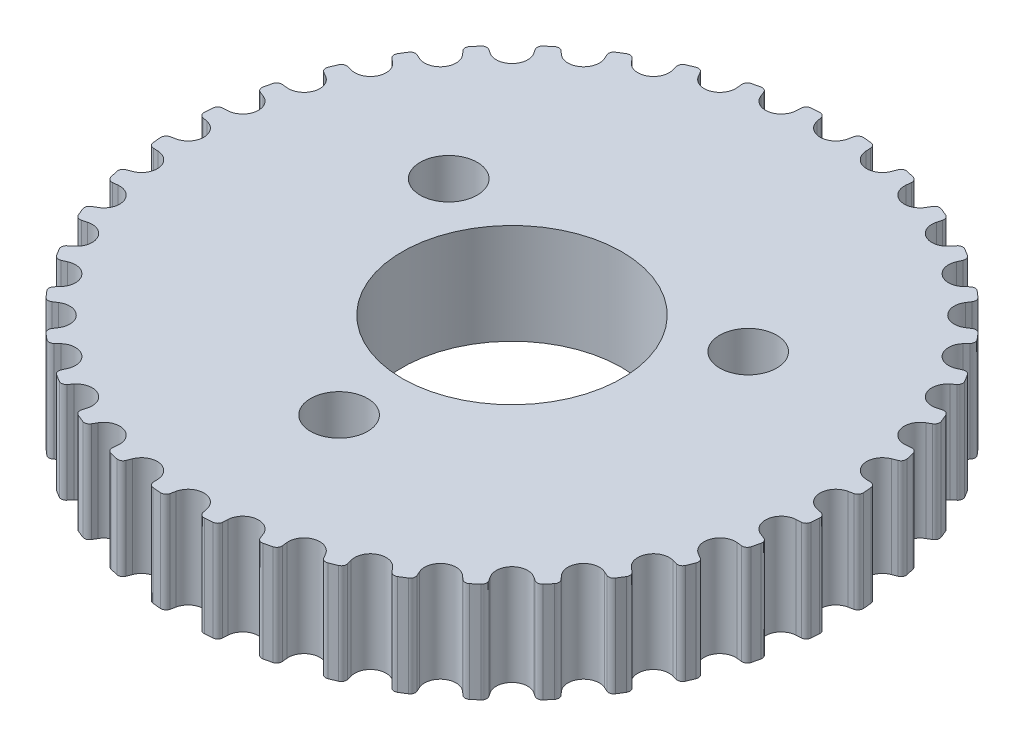
SolidWorks part; units mm, degrees
ref_plane "Front Plane" through (0, 0, 0) normal (0, 0, 1) x (1, 0, 0)
ref_plane "Top Plane" through (0, 0, 0) normal (0, 1, 0) x (1, 0, 0)
ref_plane "Right Plane" through (0, 0, 0) normal (1, 0, 0) x (0, 0, -1)
sketch "Sketch1" plane through (0, 0, 0) normal (0, 1, 0) x (1, 0, 0)
  circle A0 centre (0, 0) radius 19.0986
  dimension "D1" = 38.1972
extrude "Boss-Extrude1" add sketch "Sketch1" along normal blind 5.8
sketch "Sketch2" plane through (0, 5.8, 0) normal (0, 1, 0) x (1, 0, 0)
  line L0 (0, 0) -> (0, 19.0986) construction
  line L1 (-0.89, 18.5387) -> (-0.95, 18.82)
  line L2 (-2.9877, 18.8635) -> (-2.9877, 19.0986)
  line L3 (-2.9877, 19.0986) -> (2.9877, 19.0986)
  line L4 (0.89, 18.5387) -> (0.95, 18.82)
  line L5 (2.9877, 18.8635) -> (2.9877, 19.0986)
  circle A0 centre (0, 0) radius 19.0986 construction
  arc A1 (0.89, 18.5387) -> (-0.89, 18.5387) centre (0, 18.7286) cw
  arc A2 (-0.95, 18.82) -> (-1.2632, 19.0568) centre (-1.2434, 18.7574) ccw
  arc A4 (0.95, 18.82) -> (1.2632, 19.0568) centre (1.2434, 18.7574) cw
  arc A5 (-1.2632, 19.0568) -> (-2.9877, 18.8635) centre (0, 0) ccw
  arc A6 (1.2632, 19.0568) -> (2.9877, 18.8635) centre (0, 0) cw
  circle A8 centre (0, 0) radius 19.0986 construction
  point P11 (0, 19.0986)
  point P19 (0, 17.8186)
  dimension "D3" = 0.3
  dimension "D5" = 0.91
  dimension "D2" = 0.95
  dimension "D4" = 1.28
  dimension "D6" = 9
extrude "Cut-Extrude1" cut sketch "Sketch2" against normal through all
pattern_circular "CirPattern1" count 40 over 360 about axis through (0, 0, 0) along (0, 1, 0) of "Cut-Extrude1"
sketch "Sketch3" plane through (0, 0, 0) normal (0, -1, 0) x (1, 0, 0)
  circle A0 centre (0, 0) radius 6.35
  dimension "D1" = 12.7
extrude "Cut-Extrude2" cut sketch "Sketch3" against normal through all
sketch "Sketch4" plane through (0, 0, 0) normal (0, -1, 0) x (1, 0, 0)
  line L0 (0, 0) -> (0, 10) construction
  circle A0 centre (0, 10) radius 1.65
  circle A1 centre (8.6603, -5) radius 1.65
  circle A2 centre (-8.6603, -5) radius 1.65
  point P14 (0, 0)
  dimension "D1" = 3.3
  dimension "D2" = 10
  dimension "D3" = 3
extrude "Cut-Extrude3" cut sketch "Sketch4" against normal through all
sketch "Sketch5" plane through (0, 0, 0) normal (0, -1, 0) x (1, 0, 0)
  line L80 (-18.8409, 0.8522) -> (-18.5596, 0.7922)
  line L81 (-18.8409, 0.8522) -> (-18.5596, 0.7922)
  line L82 (-18.5596, -0.7922) -> (-18.8409, -0.8522)
  line L83 (-18.5596, -0.7922) -> (-18.8409, -0.8522)
  line L84 (-18.7423, -2.1057) -> (-18.455, -2.1209)
  line L85 (-18.7423, -2.1057) -> (-18.455, -2.1209)
  line L86 (-18.2071, -3.6858) -> (-18.4756, -3.7891)
  line L87 (-18.2071, -3.6858) -> (-18.4756, -3.7891)
  line L88 (-18.1821, -5.0117) -> (-17.896, -4.9818)
  line L89 (-18.1821, -5.0117) -> (-17.896, -4.9818)
  line L90 (-17.4064, -6.4886) -> (-17.6554, -6.6327)
  line L91 (-17.4064, -6.4886) -> (-17.6554, -6.6327)
  line L92 (-17.1743, -7.7943) -> (-16.8963, -7.72)
  line L93 (-17.1743, -7.7943) -> (-16.8963, -7.72)
  line L94 (-16.177, -9.1317) -> (-16.4005, -9.3129)
  line L95 (-16.177, -9.1317) -> (-16.4005, -9.3129)
  line L96 (-15.7435, -10.385) -> (-15.4806, -10.2682)
  line L97 (-15.7435, -10.385) -> (-15.4806, -10.2682)
  line L98 (-14.5494, -11.5499) -> (-14.7417, -11.7639)
  line L99 (-14.5494, -11.5499) -> (-14.7417, -11.7639)
  line L100 (-13.9251, -12.7199) -> (-13.6837, -12.5634)
  line L101 (-13.9251, -12.7199) -> (-13.6837, -12.5634)
  line L102 (-12.5634, -13.6837) -> (-12.7199, -13.9251)
  line L103 (-12.5634, -13.6837) -> (-12.7199, -13.9251)
  line L104 (-11.7639, -14.7417) -> (-11.5499, -14.5494)
  line L105 (-11.7639, -14.7417) -> (-11.5499, -14.5494)
  line L106 (-10.2682, -15.4806) -> (-10.385, -15.7435)
  line L107 (-10.2682, -15.4806) -> (-10.385, -15.7435)
  line L108 (-9.3129, -16.4005) -> (-9.1317, -16.177)
  line L109 (-9.3129, -16.4005) -> (-9.1317, -16.177)
  line L110 (-7.72, -16.8963) -> (-7.7943, -17.1743)
  line L111 (-7.72, -16.8963) -> (-7.7943, -17.1743)
  line L112 (-6.6327, -17.6554) -> (-6.4886, -17.4064)
  line L113 (-6.6327, -17.6554) -> (-6.4886, -17.4064)
  line L114 (-4.9818, -17.896) -> (-5.0117, -18.1821)
  line L115 (-4.9818, -17.896) -> (-5.0117, -18.1821)
  line L116 (-3.7891, -18.4756) -> (-3.6858, -18.2071)
  line L117 (-3.7891, -18.4756) -> (-3.6858, -18.2071)
  line L118 (-2.1209, -18.455) -> (-2.1057, -18.7423)
  line L119 (-2.1209, -18.455) -> (-2.1057, -18.7423)
  line L120 (6.4886, -17.4064) -> (6.6327, -17.6554)
  line L121 (7.7943, -17.1743) -> (7.72, -16.8963)
  line L122 (9.1317, -16.177) -> (9.3129, -16.4005)
  line L123 (10.385, -15.7435) -> (10.2682, -15.4806)
  line L124 (11.5499, -14.5494) -> (11.7639, -14.7417)
  line L125 (12.7199, -13.9251) -> (12.5634, -13.6837)
  line L126 (13.6837, -12.5634) -> (13.9251, -12.7199)
  line L127 (14.7417, -11.7639) -> (14.5494, -11.5499)
  line L128 (15.4806, -10.2682) -> (15.7435, -10.385)
  line L129 (16.4005, -9.3129) -> (16.177, -9.1317)
  line L130 (16.8963, -7.72) -> (17.1743, -7.7943)
  line L131 (17.6554, -6.6327) -> (17.4064, -6.4886)
  line L132 (17.896, -4.9818) -> (18.1821, -5.0117)
  line L133 (18.4756, -3.7891) -> (18.2071, -3.6858)
  line L134 (18.455, -2.1209) -> (18.7423, -2.1057)
  line L135 (18.8409, -0.8522) -> (18.5596, -0.7922)
  line L136 (18.5596, 0.7922) -> (18.8409, 0.8522)
  line L137 (18.7423, 2.1057) -> (18.455, 2.1209)
  line L138 (18.2071, 3.6858) -> (18.4756, 3.7891)
  line L139 (18.1821, 5.0117) -> (17.896, 4.9818)
  line L140 (17.4064, 6.4886) -> (17.6554, 6.6327)
  line L141 (17.1743, 7.7943) -> (16.8963, 7.72)
  line L142 (16.177, 9.1317) -> (16.4005, 9.3129)
  line L143 (15.7435, 10.385) -> (15.4806, 10.2682)
  line L144 (14.5494, 11.5499) -> (14.7417, 11.7639)
  line L145 (13.9251, 12.7199) -> (13.6837, 12.5634)
  line L146 (12.5634, 13.6837) -> (12.7199, 13.9251)
  line L147 (11.7639, 14.7417) -> (11.5499, 14.5494)
  line L148 (10.2682, 15.4806) -> (10.385, 15.7435)
  line L149 (9.3129, 16.4005) -> (9.1317, 16.177)
  line L150 (7.72, 16.8963) -> (7.7943, 17.1743)
  line L151 (6.6327, 17.6554) -> (6.4886, 17.4064)
  line L152 (4.9818, 17.896) -> (5.0117, 18.1821)
  line L153 (3.7891, 18.4756) -> (3.6858, 18.2071)
  line L154 (2.1209, 18.455) -> (2.1057, 18.7423)
  line L155 (0.8522, 18.8409) -> (0.7922, 18.5596)
  line L156 (-0.7922, 18.5596) -> (-0.8522, 18.8409)
  line L157 (-2.1057, 18.7423) -> (-2.1209, 18.455)
  line L158 (-3.6858, 18.2071) -> (-3.7891, 18.4756)
  line L159 (-5.0117, 18.1821) -> (-4.9818, 17.896)
  line L160 (-6.4886, 17.4064) -> (-6.6327, 17.6554)
  line L161 (-7.7943, 17.1743) -> (-7.72, 16.8963)
  line L162 (-9.1317, 16.177) -> (-9.3129, 16.4005)
  line L163 (-10.385, 15.7435) -> (-10.2682, 15.4806)
  line L164 (-11.5499, 14.5494) -> (-11.7639, 14.7417)
  line L165 (-12.7199, 13.9251) -> (-12.5634, 13.6837)
  line L166 (-13.6837, 12.5634) -> (-13.9251, 12.7199)
  line L167 (-14.7417, 11.7639) -> (-14.5494, 11.5499)
  line L168 (-15.4806, 10.2682) -> (-15.7435, 10.385)
  line L169 (-16.4005, 9.3129) -> (-16.177, 9.1317)
  line L170 (-16.8963, 7.72) -> (-17.1743, 7.7943)
  line L171 (-17.6554, 6.6327) -> (-17.4064, 6.4886)
  line L172 (-17.896, 4.9818) -> (-18.1821, 5.0117)
  line L173 (-18.4756, 3.7891) -> (-18.2071, 3.6858)
  line L174 (-18.455, 2.1209) -> (-18.7423, 2.1057)
  line L175 (-0.8522, -18.8409) -> (-0.7922, -18.5596)
  line L176 (0.7922, -18.5596) -> (0.8522, -18.8409)
  line L177 (2.1057, -18.7423) -> (2.1209, -18.455)
  line L178 (3.6858, -18.2071) -> (3.7891, -18.4756)
  line L179 (5.0117, -18.1821) -> (4.9818, -17.896)
  line L180 (6.4886, -17.4064) -> (6.6327, -17.6554)
  line L181 (7.7943, -17.1743) -> (7.72, -16.8963)
  line L182 (9.1317, -16.177) -> (9.3129, -16.4005)
  line L183 (10.385, -15.7435) -> (10.2682, -15.4806)
  line L184 (11.5499, -14.5494) -> (11.7639, -14.7417)
  line L185 (12.7199, -13.9251) -> (12.5634, -13.6837)
  line L186 (13.6837, -12.5634) -> (13.9251, -12.7199)
  line L187 (14.7417, -11.7639) -> (14.5494, -11.5499)
  line L188 (15.4806, -10.2682) -> (15.7435, -10.385)
  line L189 (16.4005, -9.3129) -> (16.177, -9.1317)
  line L190 (16.8963, -7.72) -> (17.1743, -7.7943)
  line L191 (17.6554, -6.6327) -> (17.4064, -6.4886)
  line L192 (17.896, -4.9818) -> (18.1821, -5.0117)
  line L193 (18.4756, -3.7891) -> (18.2071, -3.6858)
  line L194 (18.455, -2.1209) -> (18.7423, -2.1057)
  line L195 (18.8409, -0.8522) -> (18.5596, -0.7922)
  line L196 (18.5596, 0.7922) -> (18.8409, 0.8522)
  line L197 (18.7423, 2.1057) -> (18.455, 2.1209)
  line L198 (18.2071, 3.6858) -> (18.4756, 3.7891)
  line L199 (18.1821, 5.0117) -> (17.896, 4.9818)
  line L200 (17.4064, 6.4886) -> (17.6554, 6.6327)
  line L201 (17.1743, 7.7943) -> (16.8963, 7.72)
  line L202 (16.177, 9.1317) -> (16.4005, 9.3129)
  line L203 (15.7435, 10.385) -> (15.4806, 10.2682)
  line L204 (14.5494, 11.5499) -> (14.7417, 11.7639)
  line L205 (13.9251, 12.7199) -> (13.6837, 12.5634)
  line L206 (12.5634, 13.6837) -> (12.7199, 13.9251)
  line L207 (11.7639, 14.7417) -> (11.5499, 14.5494)
  line L208 (10.2682, 15.4806) -> (10.385, 15.7435)
  line L209 (9.3129, 16.4005) -> (9.1317, 16.177)
  line L210 (7.72, 16.8963) -> (7.7943, 17.1743)
  line L211 (6.6327, 17.6554) -> (6.4886, 17.4064)
  line L212 (4.9818, 17.896) -> (5.0117, 18.1821)
  line L213 (3.7891, 18.4756) -> (3.6858, 18.2071)
  line L214 (2.1209, 18.455) -> (2.1057, 18.7423)
  line L215 (0.8522, 18.8409) -> (0.7922, 18.5596)
  line L216 (-0.7922, 18.5596) -> (-0.8522, 18.8409)
  line L217 (-2.1057, 18.7423) -> (-2.1209, 18.455)
  line L218 (-3.6858, 18.2071) -> (-3.7891, 18.4756)
  line L219 (-5.0117, 18.1821) -> (-4.9818, 17.896)
  line L220 (-6.4886, 17.4064) -> (-6.6327, 17.6554)
  line L221 (-7.7943, 17.1743) -> (-7.72, 16.8963)
  line L222 (-9.1317, 16.177) -> (-9.3129, 16.4005)
  line L223 (-10.385, 15.7435) -> (-10.2682, 15.4806)
  line L224 (-11.5499, 14.5494) -> (-11.7639, 14.7417)
  line L225 (-12.7199, 13.9251) -> (-12.5634, 13.6837)
  line L226 (-13.6837, 12.5634) -> (-13.9251, 12.7199)
  line L227 (-14.7417, 11.7639) -> (-14.5494, 11.5499)
  line L228 (-15.4806, 10.2682) -> (-15.7435, 10.385)
  line L229 (-16.4005, 9.3129) -> (-16.177, 9.1317)
  line L230 (-16.8963, 7.72) -> (-17.1743, 7.7943)
  line L231 (-17.6554, 6.6327) -> (-17.4064, 6.4886)
  line L232 (-17.896, 4.9818) -> (-18.1821, 5.0117)
  line L233 (-18.4756, 3.7891) -> (-18.2071, 3.6858)
  line L234 (-18.455, 2.1209) -> (-18.7423, 2.1057)
  line L235 (-0.8522, -18.8409) -> (-0.7922, -18.5596)
  line L236 (0.7922, -18.5596) -> (0.8522, -18.8409)
  line L237 (2.1057, -18.7423) -> (2.1209, -18.455)
  line L238 (3.6858, -18.2071) -> (3.7891, -18.4756)
  line L239 (5.0117, -18.1821) -> (4.9818, -17.896)
  circle A120 centre (0, 0) radius 17.8186
  arc A121 (12.4795, 13.7381) -> (13.7381, 12.4795) centre (13.2431, 13.2431) ccw construction
  arc A162 (-19.1566, 1.2699) -> (-18.8409, 0.8522) centre (-18.7574, 1.2434) ccw
  arc A163 (-19.1566, 1.2699) -> (-18.8409, 0.8522) centre (-18.7574, 1.2434) ccw
  arc A164 (-18.5596, -0.7922) -> (-18.5596, 0.7922) centre (-18.7286, 0) ccw
  arc A165 (-18.5596, -0.7922) -> (-18.5596, 0.7922) centre (-18.7286, 0) ccw
  arc A166 (-18.8409, -0.8522) -> (-19.1566, -1.2699) centre (-18.7574, -1.2434) ccw
  arc A167 (-18.8409, -0.8522) -> (-19.1566, -1.2699) centre (-18.7574, -1.2434) ccw
  arc A168 (-19.1566, -1.2699) -> (-19.1194, -1.7425) centre (0, 0) ccw
  arc A169 (-19.1566, -1.2699) -> (-19.1194, -1.7425) centre (0, 0) ccw
  arc A170 (-19.1194, -1.7425) -> (-18.7423, -2.1057) centre (-18.721, -1.7062) ccw
  arc A171 (-19.1194, -1.7425) -> (-18.7423, -2.1057) centre (-18.721, -1.7062) ccw
  arc A172 (-18.2071, -3.6858) -> (-18.455, -2.1209) centre (-18.498, -2.9298) ccw
  arc A173 (-18.2071, -3.6858) -> (-18.455, -2.1209) centre (-18.498, -2.9298) ccw
  arc A174 (-18.4756, -3.7891) -> (-18.7221, -4.251) centre (-18.332, -4.1624) ccw
  arc A175 (-18.4756, -3.7891) -> (-18.7221, -4.251) centre (-18.332, -4.1624) ccw
  arc A176 (-18.7221, -4.251) -> (-18.6114, -4.712) centre (0, 0) ccw
  arc A177 (-18.7221, -4.251) -> (-18.6114, -4.712) centre (0, 0) ccw
  arc A178 (-18.6114, -4.712) -> (-18.1821, -5.0117) centre (-18.2236, -4.6138) ccw
  arc A179 (-18.6114, -4.712) -> (-18.1821, -5.0117) centre (-18.2236, -4.6138) ccw
  arc A180 (-17.4064, -6.4886) -> (-17.896, -4.9818) centre (-17.812, -5.7875) ccw
  arc A181 (-17.4064, -6.4886) -> (-17.896, -4.9818) centre (-17.812, -5.7875) ccw
  arc A182 (-17.6554, -6.6327) -> (-17.8266, -7.1274) centre (-17.4551, -6.9789) ccw
  arc A183 (-17.6554, -6.6327) -> (-17.8266, -7.1274) centre (-17.4551, -6.9789) ccw
  arc A184 (-17.8266, -7.1274) -> (-17.6451, -7.5654) centre (0, 0) ccw
  arc A185 (-17.8266, -7.1274) -> (-17.6451, -7.5654) centre (0, 0) ccw
  arc A186 (-17.6451, -7.5654) -> (-17.1743, -7.7943) centre (-17.2775, -7.4078) ccw
  arc A187 (-17.6451, -7.5654) -> (-17.1743, -7.7943) centre (-17.2775, -7.4078) ccw
  arc A188 (-16.177, -9.1317) -> (-16.8963, -7.72) centre (-16.6873, -8.5026) ccw
  arc A189 (-16.177, -9.1317) -> (-16.8963, -7.72) centre (-16.6873, -8.5026) ccw
  arc A190 (-16.4005, -9.3129) -> (-16.4921, -9.8283) centre (-16.1485, -9.6236) ccw
  arc A191 (-16.4005, -9.3129) -> (-16.4921, -9.8283) centre (-16.1485, -9.6236) ccw
  arc A192 (-16.4921, -9.8283) -> (-16.2444, -10.2326) centre (0, 0) ccw
  arc A193 (-16.4921, -9.8283) -> (-16.2444, -10.2326) centre (0, 0) ccw
  arc A194 (-16.2444, -10.2326) -> (-15.7435, -10.385) centre (-15.9059, -10.0194) ccw
  arc A195 (-16.2444, -10.2326) -> (-15.7435, -10.385) centre (-15.9059, -10.0194) ccw
  arc A196 (-14.5494, -11.5499) -> (-15.4806, -10.2682) centre (-15.1518, -11.0084) ccw
  arc A197 (-14.5494, -11.5499) -> (-15.4806, -10.2682) centre (-15.1518, -11.0084) ccw
  arc A198 (-14.7417, -11.7639) -> (-14.7516, -12.2873) centre (-14.4442, -12.0313) ccw
  arc A199 (-14.7417, -11.7639) -> (-14.7516, -12.2873) centre (-14.4442, -12.0313) ccw
  arc A200 (-14.7516, -12.2873) -> (-14.4436, -12.6478) centre (0, 0) ccw
  arc A201 (-14.7516, -12.2873) -> (-14.4436, -12.6478) centre (0, 0) ccw
  arc A202 (-14.4436, -12.6478) -> (-13.9251, -12.7199) centre (-14.1427, -12.3843) ccw
  arc A203 (-14.4436, -12.6478) -> (-13.9251, -12.7199) centre (-14.1427, -12.3843) ccw
  arc A204 (-12.5634, -13.6837) -> (-13.6837, -12.5634) centre (-13.2431, -13.2431) ccw
  arc A205 (-12.5634, -13.6837) -> (-13.6837, -12.5634) centre (-13.2431, -13.2431) ccw
  arc A206 (-12.7199, -13.9251) -> (-12.6478, -14.4436) centre (-12.3843, -14.1427) ccw
  arc A207 (-12.7199, -13.9251) -> (-12.6478, -14.4436) centre (-12.3843, -14.1427) ccw
  arc A208 (-12.6478, -14.4436) -> (-12.2873, -14.7516) centre (0, 0) ccw
  arc A209 (-12.6478, -14.4436) -> (-12.2873, -14.7516) centre (0, 0) ccw
  arc A210 (-12.2873, -14.7516) -> (-11.7639, -14.7417) centre (-12.0313, -14.4442) ccw
  arc A211 (-12.2873, -14.7516) -> (-11.7639, -14.7417) centre (-12.0313, -14.4442) ccw
  arc A212 (-10.2682, -15.4806) -> (-11.5499, -14.5494) centre (-11.0084, -15.1518) ccw
  arc A213 (-10.2682, -15.4806) -> (-11.5499, -14.5494) centre (-11.0084, -15.1518) ccw
  arc A214 (-10.385, -15.7435) -> (-10.2326, -16.2444) centre (-10.0194, -15.9059) ccw
  arc A215 (-10.385, -15.7435) -> (-10.2326, -16.2444) centre (-10.0194, -15.9059) ccw
  arc A216 (-10.2326, -16.2444) -> (-9.8283, -16.4921) centre (0, 0) ccw
  arc A217 (-10.2326, -16.2444) -> (-9.8283, -16.4921) centre (0, 0) ccw
  arc A218 (-9.8283, -16.4921) -> (-9.3129, -16.4005) centre (-9.6236, -16.1485) ccw
  arc A219 (-9.8283, -16.4921) -> (-9.3129, -16.4005) centre (-9.6236, -16.1485) ccw
  arc A220 (-7.72, -16.8963) -> (-9.1317, -16.177) centre (-8.5026, -16.6873) ccw
  arc A221 (-7.72, -16.8963) -> (-9.1317, -16.177) centre (-8.5026, -16.6873) ccw
  arc A222 (-7.7943, -17.1743) -> (-7.5654, -17.6451) centre (-7.4078, -17.2775) ccw
  arc A223 (-7.7943, -17.1743) -> (-7.5654, -17.6451) centre (-7.4078, -17.2775) ccw
  arc A224 (-7.5654, -17.6451) -> (-7.1274, -17.8266) centre (0, 0) ccw
  arc A225 (-7.5654, -17.6451) -> (-7.1274, -17.8266) centre (0, 0) ccw
  arc A226 (-7.1274, -17.8266) -> (-6.6327, -17.6554) centre (-6.9789, -17.4551) ccw
  arc A227 (-7.1274, -17.8266) -> (-6.6327, -17.6554) centre (-6.9789, -17.4551) ccw
  arc A228 (-4.9818, -17.896) -> (-6.4886, -17.4064) centre (-5.7875, -17.812) ccw
  arc A229 (-4.9818, -17.896) -> (-6.4886, -17.4064) centre (-5.7875, -17.812) ccw
  arc A230 (-5.0117, -18.1821) -> (-4.712, -18.6114) centre (-4.6138, -18.2236) ccw
  arc A231 (-5.0117, -18.1821) -> (-4.712, -18.6114) centre (-4.6138, -18.2236) ccw
  arc A232 (-4.712, -18.6114) -> (-4.251, -18.7221) centre (0, 0) ccw
  arc A233 (-4.712, -18.6114) -> (-4.251, -18.7221) centre (0, 0) ccw
  arc A234 (-4.251, -18.7221) -> (-3.7891, -18.4756) centre (-4.1624, -18.332) ccw
  arc A235 (-4.251, -18.7221) -> (-3.7891, -18.4756) centre (-4.1624, -18.332) ccw
  arc A236 (-2.1209, -18.455) -> (-3.6858, -18.2071) centre (-2.9298, -18.498) ccw
  arc A237 (-2.1209, -18.455) -> (-3.6858, -18.2071) centre (-2.9298, -18.498) ccw
  arc A238 (-2.1057, -18.7423) -> (-1.7425, -19.1194) centre (-1.7062, -18.721) ccw
  arc A239 (-2.1057, -18.7423) -> (-1.7425, -19.1194) centre (-1.7062, -18.721) ccw
  arc A240 (6.6327, -17.6554) -> (7.1274, -17.8266) centre (6.9789, -17.4551) ccw
  arc A241 (7.1274, -17.8266) -> (7.5654, -17.6451) centre (0, 0) ccw
  arc A242 (7.5654, -17.6451) -> (7.7943, -17.1743) centre (7.4078, -17.2775) ccw
  arc A243 (9.1317, -16.177) -> (7.72, -16.8963) centre (8.5026, -16.6873) ccw
  arc A244 (9.3129, -16.4005) -> (9.8283, -16.4921) centre (9.6236, -16.1485) ccw
  arc A245 (9.8283, -16.4921) -> (10.2326, -16.2444) centre (0, 0) ccw
  arc A246 (10.2326, -16.2444) -> (10.385, -15.7435) centre (10.0194, -15.9059) ccw
  arc A247 (11.5499, -14.5494) -> (10.2682, -15.4806) centre (11.0084, -15.1518) ccw
  arc A248 (11.7639, -14.7417) -> (12.2873, -14.7516) centre (12.0313, -14.4442) ccw
  arc A249 (12.2873, -14.7516) -> (12.6478, -14.4436) centre (0, 0) ccw
  arc A250 (12.6478, -14.4436) -> (12.7199, -13.9251) centre (12.3843, -14.1427) ccw
  arc A251 (13.6837, -12.5634) -> (12.5634, -13.6837) centre (13.2431, -13.2431) ccw
  arc A252 (13.9251, -12.7199) -> (14.4436, -12.6478) centre (14.1427, -12.3843) ccw
  arc A253 (14.4436, -12.6478) -> (14.7516, -12.2873) centre (0, 0) ccw
  arc A254 (14.7516, -12.2873) -> (14.7417, -11.7639) centre (14.4442, -12.0313) ccw
  arc A255 (15.4806, -10.2682) -> (14.5494, -11.5499) centre (15.1518, -11.0084) ccw
  arc A256 (15.7435, -10.385) -> (16.2444, -10.2326) centre (15.9059, -10.0194) ccw
  arc A257 (16.2444, -10.2326) -> (16.4921, -9.8283) centre (0, 0) ccw
  arc A258 (16.4921, -9.8283) -> (16.4005, -9.3129) centre (16.1485, -9.6236) ccw
  arc A259 (16.8963, -7.72) -> (16.177, -9.1317) centre (16.6873, -8.5026) ccw
  arc A260 (17.1743, -7.7943) -> (17.6451, -7.5654) centre (17.2775, -7.4078) ccw
  arc A261 (17.6451, -7.5654) -> (17.8266, -7.1274) centre (0, 0) ccw
  arc A262 (17.8266, -7.1274) -> (17.6554, -6.6327) centre (17.4551, -6.9789) ccw
  arc A263 (17.896, -4.9818) -> (17.4064, -6.4886) centre (17.812, -5.7875) ccw
  arc A264 (18.1821, -5.0117) -> (18.6114, -4.712) centre (18.2236, -4.6138) ccw
  arc A265 (18.6114, -4.712) -> (18.7221, -4.251) centre (0, 0) ccw
  arc A266 (18.7221, -4.251) -> (18.4756, -3.7891) centre (18.332, -4.1624) ccw
  arc A267 (18.455, -2.1209) -> (18.2071, -3.6858) centre (18.498, -2.9298) ccw
  arc A268 (18.7423, -2.1057) -> (19.1194, -1.7425) centre (18.721, -1.7062) ccw
  arc A269 (19.1194, -1.7425) -> (19.1566, -1.2699) centre (0, 0) ccw
  arc A270 (19.1566, -1.2699) -> (18.8409, -0.8522) centre (18.7574, -1.2434) ccw
  arc A271 (18.5596, 0.7922) -> (18.5596, -0.7922) centre (18.7286, 0) ccw
  arc A272 (18.8409, 0.8522) -> (19.1566, 1.2699) centre (18.7574, 1.2434) ccw
  arc A273 (19.1566, 1.2699) -> (19.1194, 1.7425) centre (0, 0) ccw
  arc A274 (19.1194, 1.7425) -> (18.7423, 2.1057) centre (18.721, 1.7062) ccw
  arc A275 (18.2071, 3.6858) -> (18.455, 2.1209) centre (18.498, 2.9298) ccw
  arc A276 (18.4756, 3.7891) -> (18.7221, 4.251) centre (18.332, 4.1624) ccw
  arc A277 (18.7221, 4.251) -> (18.6114, 4.712) centre (0, 0) ccw
  arc A278 (18.6114, 4.712) -> (18.1821, 5.0117) centre (18.2236, 4.6138) ccw
  arc A279 (17.4064, 6.4886) -> (17.896, 4.9818) centre (17.812, 5.7875) ccw
  arc A280 (17.6554, 6.6327) -> (17.8266, 7.1274) centre (17.4551, 6.9789) ccw
  arc A281 (17.8266, 7.1274) -> (17.6451, 7.5654) centre (0, 0) ccw
  arc A282 (17.6451, 7.5654) -> (17.1743, 7.7943) centre (17.2775, 7.4078) ccw
  arc A283 (16.177, 9.1317) -> (16.8963, 7.72) centre (16.6873, 8.5026) ccw
  arc A284 (16.4005, 9.3129) -> (16.4921, 9.8283) centre (16.1485, 9.6236) ccw
  arc A285 (16.4921, 9.8283) -> (16.2444, 10.2326) centre (0, 0) ccw
  arc A286 (16.2444, 10.2326) -> (15.7435, 10.385) centre (15.9059, 10.0194) ccw
  arc A287 (14.5494, 11.5499) -> (15.4806, 10.2682) centre (15.1518, 11.0084) ccw
  arc A288 (14.7417, 11.7639) -> (14.7516, 12.2873) centre (14.4442, 12.0313) ccw
  arc A289 (14.7516, 12.2873) -> (14.4436, 12.6478) centre (0, 0) ccw
  arc A290 (14.4436, 12.6478) -> (13.9251, 12.7199) centre (14.1427, 12.3843) ccw
  arc A291 (12.5634, 13.6837) -> (13.6837, 12.5634) centre (13.2431, 13.2431) ccw
  arc A292 (12.7199, 13.9251) -> (12.6478, 14.4436) centre (12.3843, 14.1427) ccw
  arc A293 (12.6478, 14.4436) -> (12.2873, 14.7516) centre (0, 0) ccw
  arc A294 (12.2873, 14.7516) -> (11.7639, 14.7417) centre (12.0313, 14.4442) ccw
  arc A295 (10.2682, 15.4806) -> (11.5499, 14.5494) centre (11.0084, 15.1518) ccw
  arc A296 (10.385, 15.7435) -> (10.2326, 16.2444) centre (10.0194, 15.9059) ccw
  arc A297 (10.2326, 16.2444) -> (9.8283, 16.4921) centre (0, 0) ccw
  arc A298 (9.8283, 16.4921) -> (9.3129, 16.4005) centre (9.6236, 16.1485) ccw
  arc A299 (7.72, 16.8963) -> (9.1317, 16.177) centre (8.5026, 16.6873) ccw
  arc A300 (7.7943, 17.1743) -> (7.5654, 17.6451) centre (7.4078, 17.2775) ccw
  arc A301 (7.5654, 17.6451) -> (7.1274, 17.8266) centre (0, 0) ccw
  arc A302 (7.1274, 17.8266) -> (6.6327, 17.6554) centre (6.9789, 17.4551) ccw
  arc A303 (4.9818, 17.896) -> (6.4886, 17.4064) centre (5.7875, 17.812) ccw
  arc A304 (5.0117, 18.1821) -> (4.712, 18.6114) centre (4.6138, 18.2236) ccw
  arc A305 (4.712, 18.6114) -> (4.251, 18.7221) centre (0, 0) ccw
  arc A306 (4.251, 18.7221) -> (3.7891, 18.4756) centre (4.1624, 18.332) ccw
  arc A307 (2.1209, 18.455) -> (3.6858, 18.2071) centre (2.9298, 18.498) ccw
  arc A308 (2.1057, 18.7423) -> (1.7425, 19.1194) centre (1.7062, 18.721) ccw
  arc A309 (1.7425, 19.1194) -> (1.2699, 19.1566) centre (0, 0) ccw
  arc A310 (1.2699, 19.1566) -> (0.8522, 18.8409) centre (1.2434, 18.7574) ccw
  arc A311 (-0.7922, 18.5596) -> (0.7922, 18.5596) centre (0, 18.7286) ccw
  arc A312 (-0.8522, 18.8409) -> (-1.2699, 19.1566) centre (-1.2434, 18.7574) ccw
  arc A313 (-1.2699, 19.1566) -> (-1.7425, 19.1194) centre (0, 0) ccw
  arc A314 (-1.7425, 19.1194) -> (-2.1057, 18.7423) centre (-1.7062, 18.721) ccw
  arc A315 (-3.6858, 18.2071) -> (-2.1209, 18.455) centre (-2.9298, 18.498) ccw
  arc A316 (-3.7891, 18.4756) -> (-4.251, 18.7221) centre (-4.1624, 18.332) ccw
  arc A317 (-4.251, 18.7221) -> (-4.712, 18.6114) centre (0, 0) ccw
  arc A318 (-4.712, 18.6114) -> (-5.0117, 18.1821) centre (-4.6138, 18.2236) ccw
  arc A319 (-6.4886, 17.4064) -> (-4.9818, 17.896) centre (-5.7875, 17.812) ccw
  arc A320 (-6.6327, 17.6554) -> (-7.1274, 17.8266) centre (-6.9789, 17.4551) ccw
  arc A321 (-7.1274, 17.8266) -> (-7.5654, 17.6451) centre (0, 0) ccw
  arc A322 (-7.5654, 17.6451) -> (-7.7943, 17.1743) centre (-7.4078, 17.2775) ccw
  arc A323 (-9.1317, 16.177) -> (-7.72, 16.8963) centre (-8.5026, 16.6873) ccw
  arc A324 (-9.3129, 16.4005) -> (-9.8283, 16.4921) centre (-9.6236, 16.1485) ccw
  arc A325 (-9.8283, 16.4921) -> (-10.2326, 16.2444) centre (0, 0) ccw
  arc A326 (-10.2326, 16.2444) -> (-10.385, 15.7435) centre (-10.0194, 15.9059) ccw
  arc A327 (-11.5499, 14.5494) -> (-10.2682, 15.4806) centre (-11.0084, 15.1518) ccw
  arc A328 (-11.7639, 14.7417) -> (-12.2873, 14.7516) centre (-12.0313, 14.4442) ccw
  arc A329 (-12.2873, 14.7516) -> (-12.6478, 14.4436) centre (0, 0) ccw
  arc A330 (-12.6478, 14.4436) -> (-12.7199, 13.9251) centre (-12.3843, 14.1427) ccw
  arc A331 (-13.6837, 12.5634) -> (-12.5634, 13.6837) centre (-13.2431, 13.2431) ccw
  arc A332 (-13.9251, 12.7199) -> (-14.4436, 12.6478) centre (-14.1427, 12.3843) ccw
  arc A333 (-14.4436, 12.6478) -> (-14.7516, 12.2873) centre (0, 0) ccw
  arc A334 (-14.7516, 12.2873) -> (-14.7417, 11.7639) centre (-14.4442, 12.0313) ccw
  arc A335 (-15.4806, 10.2682) -> (-14.5494, 11.5499) centre (-15.1518, 11.0084) ccw
  arc A336 (-15.7435, 10.385) -> (-16.2444, 10.2326) centre (-15.9059, 10.0194) ccw
  arc A337 (-16.2444, 10.2326) -> (-16.4921, 9.8283) centre (0, 0) ccw
  arc A338 (-16.4921, 9.8283) -> (-16.4005, 9.3129) centre (-16.1485, 9.6236) ccw
  arc A339 (-16.8963, 7.72) -> (-16.177, 9.1317) centre (-16.6873, 8.5026) ccw
  arc A340 (-17.1743, 7.7943) -> (-17.6451, 7.5654) centre (-17.2775, 7.4078) ccw
  arc A341 (-17.6451, 7.5654) -> (-17.8266, 7.1274) centre (0, 0) ccw
  arc A342 (-17.8266, 7.1274) -> (-17.6554, 6.6327) centre (-17.4551, 6.9789) ccw
  arc A343 (-17.896, 4.9818) -> (-17.4064, 6.4886) centre (-17.812, 5.7875) ccw
  arc A344 (-18.1821, 5.0117) -> (-18.6114, 4.712) centre (-18.2236, 4.6138) ccw
  arc A345 (-18.6114, 4.712) -> (-18.7221, 4.251) centre (0, 0) ccw
  arc A346 (-18.7221, 4.251) -> (-18.4756, 3.7891) centre (-18.332, 4.1624) ccw
  arc A347 (-18.455, 2.1209) -> (-18.2071, 3.6858) centre (-18.498, 2.9298) ccw
  arc A348 (-18.7423, 2.1057) -> (-19.1194, 1.7425) centre (-18.721, 1.7062) ccw
  arc A349 (-19.1194, 1.7425) -> (-19.1566, 1.2699) centre (0, 0) ccw
  arc A350 (-1.2699, -19.1566) -> (-0.8522, -18.8409) centre (-1.2434, -18.7574) ccw
  arc A351 (0.7922, -18.5596) -> (-0.7922, -18.5596) centre (0, -18.7286) ccw
  arc A352 (0.8522, -18.8409) -> (1.2699, -19.1566) centre (1.2434, -18.7574) ccw
  arc A353 (1.2699, -19.1566) -> (1.7425, -19.1194) centre (0, 0) ccw
  arc A354 (1.7425, -19.1194) -> (2.1057, -18.7423) centre (1.7062, -18.721) ccw
  arc A355 (3.6858, -18.2071) -> (2.1209, -18.455) centre (2.9298, -18.498) ccw
  arc A356 (3.7891, -18.4756) -> (4.251, -18.7221) centre (4.1624, -18.332) ccw
  arc A357 (4.251, -18.7221) -> (4.712, -18.6114) centre (0, 0) ccw
  arc A358 (4.712, -18.6114) -> (5.0117, -18.1821) centre (4.6138, -18.2236) ccw
  arc A359 (6.4886, -17.4064) -> (4.9818, -17.896) centre (5.7875, -17.812) ccw
  arc A360 (6.6327, -17.6554) -> (7.1274, -17.8266) centre (6.9789, -17.4551) ccw
  arc A361 (7.1274, -17.8266) -> (7.5654, -17.6451) centre (0, 0) ccw
  arc A362 (7.5654, -17.6451) -> (7.7943, -17.1743) centre (7.4078, -17.2775) ccw
  arc A363 (9.1317, -16.177) -> (7.72, -16.8963) centre (8.5026, -16.6873) ccw
  arc A364 (9.3129, -16.4005) -> (9.8283, -16.4921) centre (9.6236, -16.1485) ccw
  arc A365 (9.8283, -16.4921) -> (10.2326, -16.2444) centre (0, 0) ccw
  arc A366 (10.2326, -16.2444) -> (10.385, -15.7435) centre (10.0194, -15.9059) ccw
  arc A367 (11.5499, -14.5494) -> (10.2682, -15.4806) centre (11.0084, -15.1518) ccw
  arc A368 (11.7639, -14.7417) -> (12.2873, -14.7516) centre (12.0313, -14.4442) ccw
  arc A369 (12.2873, -14.7516) -> (12.6478, -14.4436) centre (0, 0) ccw
  arc A370 (12.6478, -14.4436) -> (12.7199, -13.9251) centre (12.3843, -14.1427) ccw
  arc A371 (13.6837, -12.5634) -> (12.5634, -13.6837) centre (13.2431, -13.2431) ccw
  arc A372 (13.9251, -12.7199) -> (14.4436, -12.6478) centre (14.1427, -12.3843) ccw
  arc A373 (14.4436, -12.6478) -> (14.7516, -12.2873) centre (0, 0) ccw
  arc A374 (14.7516, -12.2873) -> (14.7417, -11.7639) centre (14.4442, -12.0313) ccw
  arc A375 (15.4806, -10.2682) -> (14.5494, -11.5499) centre (15.1518, -11.0084) ccw
  arc A376 (15.7435, -10.385) -> (16.2444, -10.2326) centre (15.9059, -10.0194) ccw
  arc A377 (16.2444, -10.2326) -> (16.4921, -9.8283) centre (0, 0) ccw
  arc A378 (16.4921, -9.8283) -> (16.4005, -9.3129) centre (16.1485, -9.6236) ccw
  arc A379 (16.8963, -7.72) -> (16.177, -9.1317) centre (16.6873, -8.5026) ccw
  arc A380 (17.1743, -7.7943) -> (17.6451, -7.5654) centre (17.2775, -7.4078) ccw
  arc A381 (17.6451, -7.5654) -> (17.8266, -7.1274) centre (0, 0) ccw
  arc A382 (17.8266, -7.1274) -> (17.6554, -6.6327) centre (17.4551, -6.9789) ccw
  arc A383 (17.896, -4.9818) -> (17.4064, -6.4886) centre (17.812, -5.7875) ccw
  arc A384 (18.1821, -5.0117) -> (18.6114, -4.712) centre (18.2236, -4.6138) ccw
  arc A385 (18.6114, -4.712) -> (18.7221, -4.251) centre (0, 0) ccw
  arc A386 (18.7221, -4.251) -> (18.4756, -3.7891) centre (18.332, -4.1624) ccw
  arc A387 (18.455, -2.1209) -> (18.2071, -3.6858) centre (18.498, -2.9298) ccw
  arc A388 (18.7423, -2.1057) -> (19.1194, -1.7425) centre (18.721, -1.7062) ccw
  arc A389 (19.1194, -1.7425) -> (19.1566, -1.2699) centre (0, 0) ccw
  arc A390 (19.1566, -1.2699) -> (18.8409, -0.8522) centre (18.7574, -1.2434) ccw
  arc A391 (18.5596, 0.7922) -> (18.5596, -0.7922) centre (18.7286, 0) ccw
  arc A392 (18.8409, 0.8522) -> (19.1566, 1.2699) centre (18.7574, 1.2434) ccw
  arc A393 (19.1566, 1.2699) -> (19.1194, 1.7425) centre (0, 0) ccw
  arc A394 (19.1194, 1.7425) -> (18.7423, 2.1057) centre (18.721, 1.7062) ccw
  arc A395 (18.2071, 3.6858) -> (18.455, 2.1209) centre (18.498, 2.9298) ccw
  arc A396 (18.4756, 3.7891) -> (18.7221, 4.251) centre (18.332, 4.1624) ccw
  arc A397 (18.7221, 4.251) -> (18.6114, 4.712) centre (0, 0) ccw
  arc A398 (18.6114, 4.712) -> (18.1821, 5.0117) centre (18.2236, 4.6138) ccw
  arc A399 (17.4064, 6.4886) -> (17.896, 4.9818) centre (17.812, 5.7875) ccw
  arc A400 (17.6554, 6.6327) -> (17.8266, 7.1274) centre (17.4551, 6.9789) ccw
  arc A401 (17.8266, 7.1274) -> (17.6451, 7.5654) centre (0, 0) ccw
  arc A402 (17.6451, 7.5654) -> (17.1743, 7.7943) centre (17.2775, 7.4078) ccw
  arc A403 (16.177, 9.1317) -> (16.8963, 7.72) centre (16.6873, 8.5026) ccw
  arc A404 (16.4005, 9.3129) -> (16.4921, 9.8283) centre (16.1485, 9.6236) ccw
  arc A405 (16.4921, 9.8283) -> (16.2444, 10.2326) centre (0, 0) ccw
  arc A406 (16.2444, 10.2326) -> (15.7435, 10.385) centre (15.9059, 10.0194) ccw
  arc A407 (14.5494, 11.5499) -> (15.4806, 10.2682) centre (15.1518, 11.0084) ccw
  arc A408 (14.7417, 11.7639) -> (14.7516, 12.2873) centre (14.4442, 12.0313) ccw
  arc A409 (14.7516, 12.2873) -> (14.4436, 12.6478) centre (0, 0) ccw
  arc A410 (14.4436, 12.6478) -> (13.9251, 12.7199) centre (14.1427, 12.3843) ccw
  arc A411 (12.5634, 13.6837) -> (13.6837, 12.5634) centre (13.2431, 13.2431) ccw
  arc A412 (12.7199, 13.9251) -> (12.6478, 14.4436) centre (12.3843, 14.1427) ccw
  arc A413 (12.6478, 14.4436) -> (12.2873, 14.7516) centre (0, 0) ccw
  arc A414 (12.2873, 14.7516) -> (11.7639, 14.7417) centre (12.0313, 14.4442) ccw
  arc A415 (10.2682, 15.4806) -> (11.5499, 14.5494) centre (11.0084, 15.1518) ccw
  arc A416 (10.385, 15.7435) -> (10.2326, 16.2444) centre (10.0194, 15.9059) ccw
  arc A417 (10.2326, 16.2444) -> (9.8283, 16.4921) centre (0, 0) ccw
  arc A418 (9.8283, 16.4921) -> (9.3129, 16.4005) centre (9.6236, 16.1485) ccw
  arc A419 (7.72, 16.8963) -> (9.1317, 16.177) centre (8.5026, 16.6873) ccw
  arc A420 (7.7943, 17.1743) -> (7.5654, 17.6451) centre (7.4078, 17.2775) ccw
  arc A421 (7.5654, 17.6451) -> (7.1274, 17.8266) centre (0, 0) ccw
  arc A422 (7.1274, 17.8266) -> (6.6327, 17.6554) centre (6.9789, 17.4551) ccw
  arc A423 (4.9818, 17.896) -> (6.4886, 17.4064) centre (5.7875, 17.812) ccw
  arc A424 (5.0117, 18.1821) -> (4.712, 18.6114) centre (4.6138, 18.2236) ccw
  arc A425 (4.712, 18.6114) -> (4.251, 18.7221) centre (0, 0) ccw
  arc A426 (4.251, 18.7221) -> (3.7891, 18.4756) centre (4.1624, 18.332) ccw
  arc A427 (2.1209, 18.455) -> (3.6858, 18.2071) centre (2.9298, 18.498) ccw
  arc A428 (2.1057, 18.7423) -> (1.7425, 19.1194) centre (1.7062, 18.721) ccw
  arc A429 (1.7425, 19.1194) -> (1.2699, 19.1566) centre (0, 0) ccw
  arc A430 (1.2699, 19.1566) -> (0.8522, 18.8409) centre (1.2434, 18.7574) ccw
  arc A431 (-0.7922, 18.5596) -> (0.7922, 18.5596) centre (0, 18.7286) ccw
  arc A432 (-0.8522, 18.8409) -> (-1.2699, 19.1566) centre (-1.2434, 18.7574) ccw
  arc A433 (-1.2699, 19.1566) -> (-1.7425, 19.1194) centre (0, 0) ccw
  arc A434 (-1.7425, 19.1194) -> (-2.1057, 18.7423) centre (-1.7062, 18.721) ccw
  arc A435 (-3.6858, 18.2071) -> (-2.1209, 18.455) centre (-2.9298, 18.498) ccw
  arc A436 (-3.7891, 18.4756) -> (-4.251, 18.7221) centre (-4.1624, 18.332) ccw
  arc A437 (-4.251, 18.7221) -> (-4.712, 18.6114) centre (0, 0) ccw
  arc A438 (-4.712, 18.6114) -> (-5.0117, 18.1821) centre (-4.6138, 18.2236) ccw
  arc A439 (-6.4886, 17.4064) -> (-4.9818, 17.896) centre (-5.7875, 17.812) ccw
  arc A440 (-6.6327, 17.6554) -> (-7.1274, 17.8266) centre (-6.9789, 17.4551) ccw
  arc A441 (-7.1274, 17.8266) -> (-7.5654, 17.6451) centre (0, 0) ccw
  arc A442 (-7.5654, 17.6451) -> (-7.7943, 17.1743) centre (-7.4078, 17.2775) ccw
  arc A443 (-9.1317, 16.177) -> (-7.72, 16.8963) centre (-8.5026, 16.6873) ccw
  arc A444 (-9.3129, 16.4005) -> (-9.8283, 16.4921) centre (-9.6236, 16.1485) ccw
  arc A445 (-9.8283, 16.4921) -> (-10.2326, 16.2444) centre (0, 0) ccw
  arc A446 (-10.2326, 16.2444) -> (-10.385, 15.7435) centre (-10.0194, 15.9059) ccw
  arc A447 (-11.5499, 14.5494) -> (-10.2682, 15.4806) centre (-11.0084, 15.1518) ccw
  arc A448 (-11.7639, 14.7417) -> (-12.2873, 14.7516) centre (-12.0313, 14.4442) ccw
  arc A449 (-12.2873, 14.7516) -> (-12.6478, 14.4436) centre (0, 0) ccw
  arc A450 (-12.6478, 14.4436) -> (-12.7199, 13.9251) centre (-12.3843, 14.1427) ccw
  arc A451 (-13.6837, 12.5634) -> (-12.5634, 13.6837) centre (-13.2431, 13.2431) ccw
  arc A452 (-13.9251, 12.7199) -> (-14.4436, 12.6478) centre (-14.1427, 12.3843) ccw
  arc A453 (-14.4436, 12.6478) -> (-14.7516, 12.2873) centre (0, 0) ccw
  arc A454 (-14.7516, 12.2873) -> (-14.7417, 11.7639) centre (-14.4442, 12.0313) ccw
  arc A455 (-15.4806, 10.2682) -> (-14.5494, 11.5499) centre (-15.1518, 11.0084) ccw
  arc A456 (-15.7435, 10.385) -> (-16.2444, 10.2326) centre (-15.9059, 10.0194) ccw
  arc A457 (-16.2444, 10.2326) -> (-16.4921, 9.8283) centre (0, 0) ccw
  arc A458 (-16.4921, 9.8283) -> (-16.4005, 9.3129) centre (-16.1485, 9.6236) ccw
  arc A459 (-16.8963, 7.72) -> (-16.177, 9.1317) centre (-16.6873, 8.5026) ccw
  arc A460 (-17.1743, 7.7943) -> (-17.6451, 7.5654) centre (-17.2775, 7.4078) ccw
  arc A461 (-17.6451, 7.5654) -> (-17.8266, 7.1274) centre (0, 0) ccw
  arc A462 (-17.8266, 7.1274) -> (-17.6554, 6.6327) centre (-17.4551, 6.9789) ccw
  arc A463 (-17.896, 4.9818) -> (-17.4064, 6.4886) centre (-17.812, 5.7875) ccw
  arc A464 (-18.1821, 5.0117) -> (-18.6114, 4.712) centre (-18.2236, 4.6138) ccw
  arc A465 (-18.6114, 4.712) -> (-18.7221, 4.251) centre (0, 0) ccw
  arc A466 (-18.7221, 4.251) -> (-18.4756, 3.7891) centre (-18.332, 4.1624) ccw
  arc A467 (-18.455, 2.1209) -> (-18.2071, 3.6858) centre (-18.498, 2.9298) ccw
  arc A468 (-18.7423, 2.1057) -> (-19.1194, 1.7425) centre (-18.721, 1.7062) ccw
  arc A469 (-19.1194, 1.7425) -> (-19.1566, 1.2699) centre (0, 0) ccw
  arc A470 (-1.2699, -19.1566) -> (-0.8522, -18.8409) centre (-1.2434, -18.7574) ccw
  arc A471 (0.7922, -18.5596) -> (-0.7922, -18.5596) centre (0, -18.7286) ccw
  arc A472 (0.8522, -18.8409) -> (1.2699, -19.1566) centre (1.2434, -18.7574) ccw
  arc A473 (1.2699, -19.1566) -> (1.7425, -19.1194) centre (0, 0) ccw
  arc A474 (1.7425, -19.1194) -> (2.1057, -18.7423) centre (1.7062, -18.721) ccw
  arc A475 (3.6858, -18.2071) -> (2.1209, -18.455) centre (2.9298, -18.498) ccw
  arc A476 (3.7891, -18.4756) -> (4.251, -18.7221) centre (4.1624, -18.332) ccw
  arc A477 (4.251, -18.7221) -> (4.712, -18.6114) centre (0, 0) ccw
  arc A478 (4.712, -18.6114) -> (5.0117, -18.1821) centre (4.6138, -18.2236) ccw
  arc A479 (6.4886, -17.4064) -> (4.9818, -17.896) centre (5.7875, -17.812) ccw
  arc A480 (-1.7425, -19.1194) -> (-1.2699, -19.1566) centre (0, 0) ccw
  arc A481 (-1.7425, -19.1194) -> (-1.2699, -19.1566) centre (0, 0) ccw
  dimension "D1" = 0.1
extrude "Boss-Extrude2" [suppressed] add sketch "Sketch5" against normal up to surface (5.8 mm away)
equation "\"smallPulleyTeeth\"= 15"
equation "\"largePulleyTeeth\"= 40"
equation "\"eighthThick\"= 2.9mm"
equation "\"D1@Sketch1\"=3*\"largePulleyTeeth\"/pi"
equation "\"D1@Boss-Extrude1\" = \"eighthThick\" * 2"
equation "\"D6@Sketch2\"=360/\"largePulleyTeeth\""
equation "\"quarterThick\"=5.9mm"
equation "\"D1@CirPattern1\"=\"largePulleyTeeth\""
equation "\"sixteenthThick\"= 1.7mm"
equation "\"OD\"= 145mm"
equation "\"puckAngle\"= 60.5deg"
equation "\"puckDiam\"= 76.5mm"
equation "\"axlePress\"= 5.9mm"
equation "\"press\"= 0.2mm"
equation "\"wheelClear\"= 0.3mm"
equation "\"10-32clear\"= 4.5mm"
equation "\"D1@Sketch4\"=\"6-32clear\""
equation "\"6-32clear\"= 3.3mm"
equation "\"8-32clear\"= 4.0mm"
